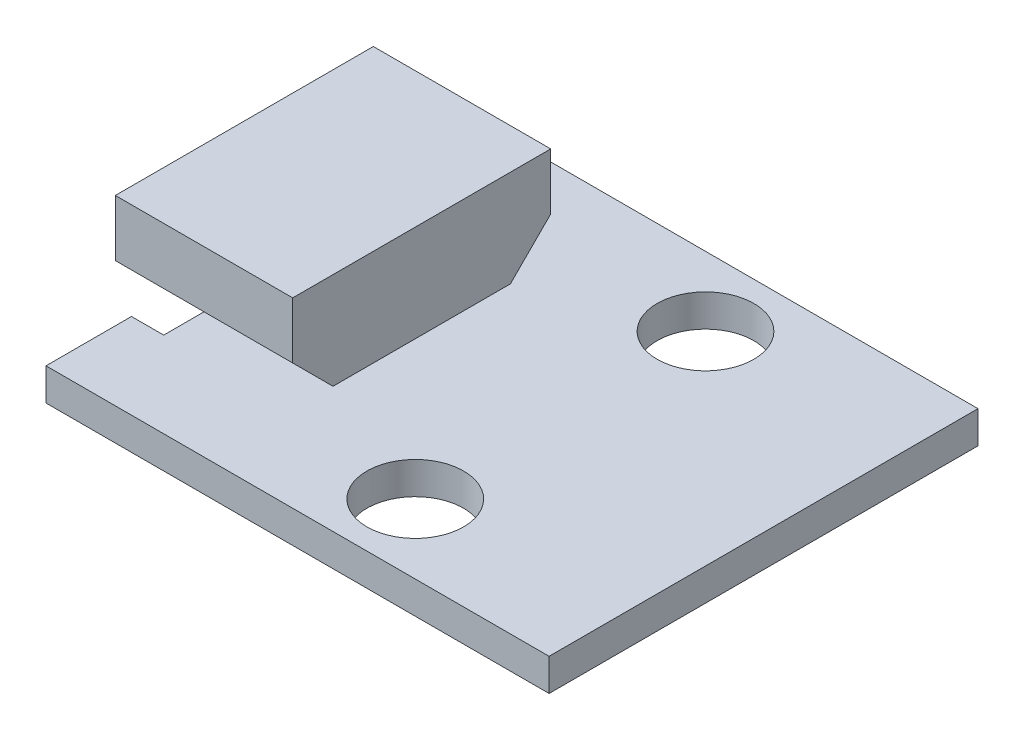
SolidWorks part; units mm, degrees
ref_plane "Front Plane" through (0, 0, 0) normal (0, 0, 1) x (1, 0, 0)
ref_plane "Top Plane" through (0, 0, 0) normal (0, 1, 0) x (1, 0, 0)
ref_plane "Right Plane" through (0, 0, 0) normal (1, 0, 0) x (0, 0, -1)
sketch "Sketch1" plane through (0, 0, 0) normal (0, 1, 0) x (1, 0, 0)
  line L0 (0, 6.65) -> (-15.6, 6.65) construction
  line L1 (0, 0) -> (-15.6, 0)
  line L2 (0, 0) -> (0, 13.3)
  line L3 (0, 13.3) -> (-15.6, 13.3)
  line L4 (-15.6, 0) -> (-15.6, 13.3)
  line L5 (-6.3, 2.15) -> (-6.3, 11.15) construction
  line L7 (-15.6, 10.65) -> (-14.6, 10.65)
  line L8 (-15.6, 10.65) -> (-15.6, 2.65)
  line L9 (-15.6, 2.65) -> (-14.6, 2.65)
  line L10 (-14.6, 10.65) -> (-14.6, 2.65)
  circle A0 centre (-6.3, 11.15) radius 1.5
  circle A1 centre (-6.3, 2.15) radius 1.5
  point P14 (-6.3, 6.65)
  dimension "D3" = 3
  dimension "D4" = 3
  dimension "D1" = 15.6
  dimension "D2" = 13.3
  dimension "D5" = 9
  dimension "D6" = 9.3
  dimension "D7" = 1
  dimension "D8" = 4
  dimension "D9" = 4
extrude "Boss-Extrude1" add sketch "Sketch1" along normal blind 1 contours L7 L10 L9 L4 L1 L2 L3 A1 A0
ref_plane "Plane1" through (-16.1, 0, 0) normal (-1, 0, 0) x (0, 0, 1)
sketch "Sketch2" plane through (-16.1, 0, 0) normal (-1, 0, 0) x (0, 0, 1)
  line L0 (-6.65, 0) -> (-6.65, 4.5) construction
  line L1 (-10.65, 0) -> (-2.65, 0) construction
  line L2 (-2.65, 4) -> (-10.65, 4)
  line L3 (-2.65, 4) -> (-2.65, 2.25)
  line L4 (-2.65, 2.25) -> (-3.9, 1)
  line L5 (-9.4, 1) -> (-3.9, 1)
  line L6 (-10.65, 2.25) -> (-2.65, 2.25) construction
  line L7 (-9.4, 1) -> (-10.65, 2.25)
  line L8 (-10.65, 2.25) -> (-10.65, 4)
  line L9 (-10.65, 1) -> (-2.65, 1) construction
  point P7 (-6.65, 4)
  point P12 (-6.65, 1)
  point P14 (-6.65, 2.25)
  dimension "D1" = 5.5
  dimension "D2" = 8
  dimension "D3" = 3
extrude "Boss-Extrude2" add sketch "Sketch2" against normal blind 5.5 separate body
sketch "Sketch3" plane through (-16.1, 0, 0) normal (-1, 0, 0) x (0, 0, 1)
  line L12 (-10.15, 3.5) -> (-10.15, 2.4571)
  line L13 (-10.15, 2.4571) -> (-9.1929, 1.5)
  line L14 (-9.1929, 1.5) -> (-4.1071, 1.5)
  line L15 (-4.1071, 1.5) -> (-3.15, 2.4571)
  line L16 (-3.15, 2.4571) -> (-3.15, 3.5)
  line L17 (-3.15, 3.5) -> (-10.15, 3.5)
  line L18 (-10.15, 3.5) -> (-10.15, 2.4571)
  line L19 (-10.15, 2.4571) -> (-9.1929, 1.5)
  line L20 (-9.1929, 1.5) -> (-4.1071, 1.5)
  line L21 (-4.1071, 1.5) -> (-3.15, 2.4571)
  line L22 (-3.15, 2.4571) -> (-3.15, 3.5)
  line L23 (-3.15, 3.5) -> (-10.15, 3.5)
  dimension "D1" = 0.5
extrude "Cut-Extrude1" cut sketch "Sketch3" against normal blind 5
